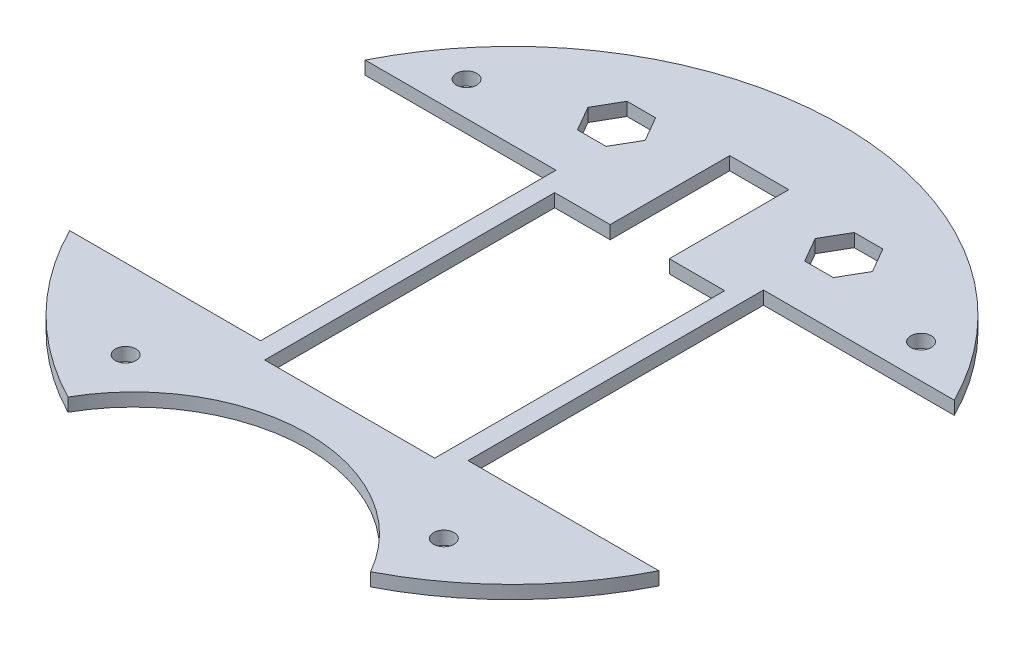
SolidWorks part; units mm, degrees
material "Acrylic (Medium-high impact)"
ref_plane "Front Plane" through (0, 0, 0) normal (0, 0, 1) x (1, 0, 0)
ref_plane "Top Plane" through (0, 0, 0) normal (0, 1, 0) x (1, 0, 0)
ref_plane "Right Plane" through (0, 0, 0) normal (1, 0, 0) x (0, 0, -1)
sketch "Sketch1" plane through (0, 0, 0) normal (0, 1, 0) x (1, 0, 0)
  line L0 (0, -83.2398) -> (-33.2911, -64.4046) construction
  line L1 (0, -83.2398) -> (0, 0) construction
  arc A0 (33.2911, -64.4046) -> (-33.2911, -64.4046) centre (0, 0) ccw
  arc A1 (33.2911, -64.4046) -> (-33.2911, -64.4046) centre (0, -83.2398) ccw
  dimension "D1" = 145
  dimension "D2" = 76.5
  dimension "D3" = 60.5
extrude "Boss-Extrude1" add sketch "Sketch1" along normal blind 2.9
sketch "solenoid placement" plane through (0, 2.9, 0) normal (0, 1, 0) x (1, 0, 0)
  line L4 (-18.7, -35.7) -> (18.7, -35.7)
  line L5 (18.7, -35.7) -> (18.7, 28.1)
  line L6 (18.7, 28.1) -> (-18.7, 28.1)
  line L7 (-18.7, 28.1) -> (-18.7, -35.7)
  line L8 (-18.7, -35.7) -> (18.7, -35.7)
  line L9 (18.7, -35.7) -> (18.7, 28.1)
  line L10 (18.7, 28.1) -> (-18.7, 28.1)
  line L11 (-18.7, 28.1) -> (-18.7, -35.7)
  circle A1 centre (0, 0) radius 72.5 construction
  arc A2 (33.2911, -64.4046) -> (-33.2911, -64.4046) centre (0, 0) ccw construction
  dimension "D1" = 0
extrude "Cut-Extrude1" cut sketch "solenoid placement" against normal through all
sketch "Sketch3" plane through (0, 2.9, 0) normal (0, 1, 0) x (1, 0, 0)
  line L4 (-34.63, -32.5) -> (-22.83, -32.5)
  line L5 (-22.83, -32.5) -> (-22.83, 32.5)
  line L6 (-22.83, 32.5) -> (-64.8074, 32.5)
  line L7 (-64.8074, -32.5) -> (-34.63, -32.5)
  line L8 (-34.63, -32.5) -> (-22.83, -32.5)
  line L9 (-22.83, -32.5) -> (-22.83, 32.5)
  line L10 (-22.83, 32.5) -> (-64.8074, 32.5)
  line L11 (-64.8074, -32.5) -> (-34.63, -32.5)
  line L12 (34.63, -32.5) -> (64.8074, -32.5)
  line L13 (64.8074, 32.5) -> (22.83, 32.5)
  line L14 (22.83, 32.5) -> (22.83, -32.5)
  line L15 (22.83, -32.5) -> (34.63, -32.5)
  line L16 (34.63, -32.5) -> (64.8074, -32.5)
  line L17 (64.8074, 32.5) -> (22.83, 32.5)
  line L18 (22.83, 32.5) -> (22.83, -32.5)
  line L19 (22.83, -32.5) -> (34.63, -32.5)
  arc A2 (-64.8074, 32.5) -> (-64.8074, -32.5) centre (0, 0) ccw
  arc A3 (-64.8074, 32.5) -> (-64.8074, -32.5) centre (0, 0) ccw
  arc A4 (64.8074, -32.5) -> (64.8074, 32.5) centre (0, 0) ccw
  arc A5 (64.8074, -32.5) -> (64.8074, 32.5) centre (0, 0) ccw
  dimension "D2" = 0
  dimension "D1" = 0
extrude "Cut-Extrude3" cut sketch "Sketch3" against normal through all
sketch "Sketch4" plane through (0, 2.9, 0) normal (0, 1, 0) x (1, 0, 0)
  line L0 (18.7, 28.1) -> (-18.7, 28.1) construction
  line L1 (-6.5, 28.1) -> (6.5, 28.1)
  line L2 (-6.5, 28.1) -> (-6.5, 54.4)
  line L3 (6.5, 54.4) -> (-6.5, 54.4) construction
  line L4 (6.5, 28.1) -> (6.5, 54.4)
  line L5 (6.5, 54.4) -> (-6.5, 54.4)
  point P6 (0, 28.1)
extrude "Cut-Extrude4" cut sketch "Sketch4" against normal through all
sketch "Sketch5" plane through (0, 2.9, 0) normal (0, 1, 0) x (1, 0, 0)
  line L6 (-18.7069, 48) -> (-21.8534, 53.45)
  line L7 (-21.8534, 53.45) -> (-28.1466, 53.45)
  line L8 (-28.1466, 53.45) -> (-31.2931, 48)
  line L9 (-31.2931, 48) -> (-28.1466, 42.55)
  line L10 (-28.1466, 42.55) -> (-21.8534, 42.55)
  line L11 (-21.8534, 42.55) -> (-18.7069, 48)
  line L12 (-18.7069, 48) -> (-21.8534, 53.45)
  line L13 (-21.8534, 53.45) -> (-28.1466, 53.45)
  line L14 (-28.1466, 53.45) -> (-31.2931, 48)
  line L15 (-31.2931, 48) -> (-28.1466, 42.55)
  line L16 (-28.1466, 42.55) -> (-21.8534, 42.55)
  line L17 (-21.8534, 42.55) -> (-18.7069, 48)
  line L18 (18.7069, 48) -> (21.8534, 42.55)
  line L19 (21.8534, 53.45) -> (18.7069, 48)
  line L20 (28.1466, 53.45) -> (21.8534, 53.45)
  line L21 (31.2931, 48) -> (28.1466, 53.45)
  line L22 (28.1466, 42.55) -> (31.2931, 48)
  line L23 (21.8534, 42.55) -> (28.1466, 42.55)
  line L24 (18.7069, 48) -> (21.8534, 42.55)
  line L25 (21.8534, 53.45) -> (18.7069, 48)
  line L26 (28.1466, 53.45) -> (21.8534, 53.45)
  line L27 (31.2931, 48) -> (28.1466, 53.45)
  line L28 (28.1466, 42.55) -> (31.2931, 48)
  line L29 (21.8534, 42.55) -> (28.1466, 42.55)
  dimension "D1" = 0
  dimension "D2" = 0
extrude "Cut-Extrude5" cut sketch "Sketch5" against normal through all
sketch "Sketch6" plane through (0, 2.9, 0) normal (0, 1, 0) x (1, 0, 0)
  circle A1 centre (35, -50) radius 2.25
  circle A2 centre (35, -50) radius 2.25
  circle A3 centre (-35, -50) radius 2.25
  circle A4 centre (-35, -50) radius 2.25
  circle A5 centre (-50, 40) radius 2.25
  circle A6 centre (-50, 40) radius 2.25
  circle A7 centre (50, 40) radius 2.25
  circle A8 centre (50, 40) radius 2.25
  dimension "D1" = 0
  dimension "D2" = 0
  dimension "D3" = 0
  dimension "D4" = 0
extrude "Cut-Extrude6" cut sketch "Sketch6" against normal through all
equation "\"smallPulleyTeeth\"= 15"
equation "\"largePulleyTeeth\"= 30"
equation "\"eighthThick\"= 2.9mm"
equation "\"sixteenthThick\" = 1.7mm"
equation "\"quarterThick\"=5.9mm"
equation "\"OD\" = 145mm"
equation "\"puckAngle\" = 60.5deg"
equation "\"D1@Sketch1\"=\"OD\""
equation "\"puckDiam\" = 76.5mm"
equation "\"D2@Sketch1\"=\"puckDiam\""
equation "\"D3@Sketch1\"=\"puckAngle\""
equation "\"D1@Boss-Extrude1\"=\"eighthThick\""
equation "\"axlePress\" = 5.9mm"
equation "\"press\" = 0.2mm"
equation "\"wheelClear\" = 0.3mm"
equation "\"10-32clear\" = 4.5mm"
equation "\"6-32clear\" = 3.3mm"
equation "\"8-32clear\" = 4.0mm"
equation "\"wheelHeight\" = 22mm"
equation "\"wheelWell\" = 65mm"
